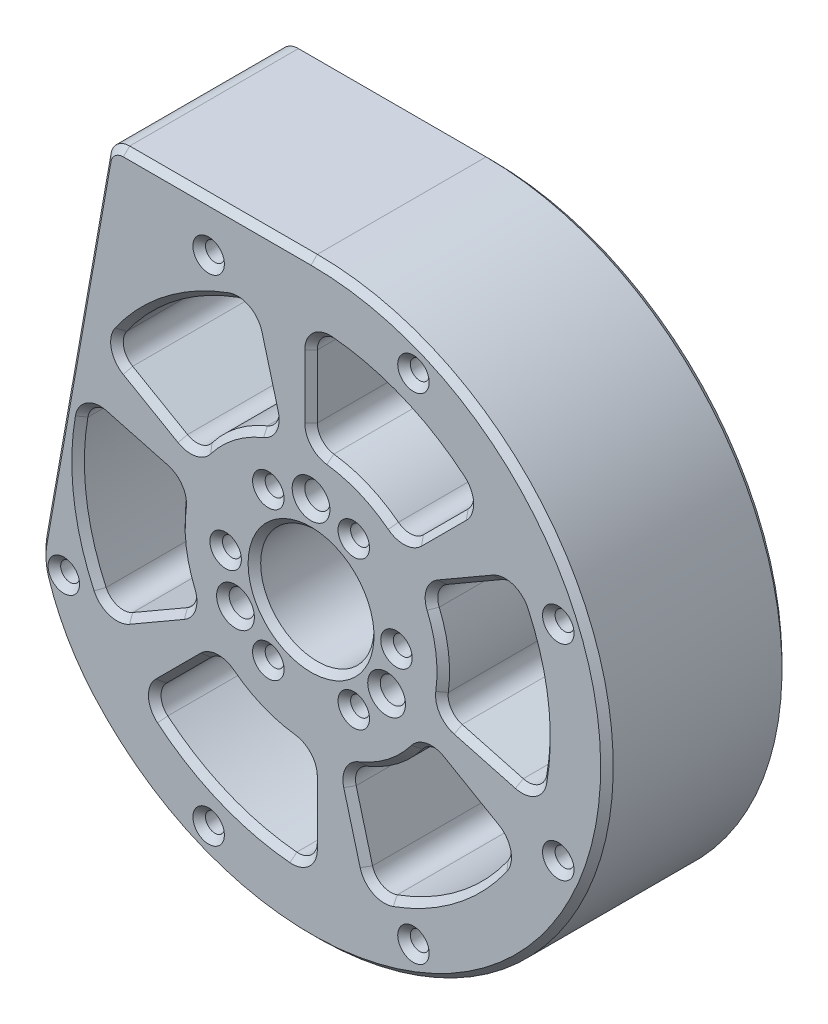
SolidWorks part; units mm, degrees
material "尼龙 101"
ref_plane "前视基准面" through (0, 0, 0) normal (0, 0, 1) x (1, 0, 0)
ref_plane "上视基准面" through (0, 0, 0) normal (0, 1, 0) x (1, 0, 0)
ref_plane "右视基准面" through (0, 0, 0) normal (1, 0, 0) x (0, 0, -1)
sketch "草图1" plane through (0, 0, 0) normal (0, 0, 1) x (1, 0, 0)
  line L0 (-29.8039, 47) -> (0, 47)
  line L1 (-75.3218, 47) -> (0, 47) construction
  line L3 (-32.7584, 44.5209) -> (-42.9535, -13.2986)
  line L6 (-43.3454, -15.5209) -> (-32.9421, 43.4791) construction
  line L7 (0, 23.8118) -> (0, 33.8674)
  line L8 (16.8375, 16.8375) -> (23.9479, 23.9479)
  line L9 (20.6216, 11.9059) -> (29.33, 16.9337)
  line L10 (23.0004, -6.1629) -> (32.7134, -8.7655)
  line L11 (20.6216, -11.9059) -> (29.33, -16.9337)
  line L12 (6.1629, -23.0004) -> (8.7655, -32.7134)
  line L13 (0, -23.8118) -> (0, -33.8674)
  line L14 (-16.8375, -16.8375) -> (-23.9479, -23.9479)
  line L15 (-20.6216, -11.9059) -> (-29.33, -16.9337)
  line L16 (-23.0004, 6.1629) -> (-32.7134, 8.7655)
  line L17 (-20.6216, 11.9059) -> (-29.33, 16.9337)
  line L18 (-6.1629, 23.0004) -> (-8.7655, 32.7134)
  arc A0 (0, 47) -> (-35.3098, -31.0197) centre (0, 0) cw
  circle A1 centre (16.264, 39.2649) radius 1.5
  circle A2 centre (16.264, 39.2649) radius 1.5
  circle A3 centre (-16.264, 39.2649) radius 1.5
  circle A4 centre (-16.264, 39.2649) radius 1.5
  circle A5 centre (-39.2649, -16.264) radius 1.5
  circle A6 centre (-39.2649, -16.264) radius 1.5
  circle A7 centre (-16.264, -39.2649) radius 1.5
  circle A8 centre (-16.264, -39.2649) radius 1.5
  circle A9 centre (16.264, -39.2649) radius 1.5
  circle A10 centre (16.264, -39.2649) radius 1.5
  circle A11 centre (39.2649, -16.264) radius 1.5
  circle A12 centre (39.2649, -16.264) radius 1.5
  circle A13 centre (39.2649, 16.264) radius 1.5
  circle A14 centre (39.2649, 16.264) radius 1.5
  circle A15 centre (0, 0) radius 9
  circle A16 centre (0, 0) radius 9
  circle A17 centre (-6.7839, 11.75) radius 1.5
  circle A18 centre (-6.7839, 11.75) radius 1.5
  circle A19 centre (6.7839, 11.75) radius 1.5
  circle A20 centre (6.7839, 11.75) radius 1.5
  circle A21 centre (-13.5677, 0) radius 1.5
  circle A22 centre (-13.5677, 0) radius 1.5
  circle A23 centre (-6.7839, -11.75) radius 1.5
  circle A24 centre (-6.7839, -11.75) radius 1.5
  circle A25 centre (6.7839, -11.75) radius 1.5
  circle A26 centre (6.7839, -11.75) radius 1.5
  circle A27 centre (13.5677, 0) radius 1.5
  circle A28 centre (13.5677, 0) radius 1.5
  circle A29 centre (0, 13.8564) radius 2
  circle A30 centre (0, 13.8564) radius 2
  circle A31 centre (12, -6.9282) radius 2
  circle A32 centre (12, -6.9282) radius 2
  circle A33 centre (-12, -6.9282) radius 2
  circle A34 centre (-12, -6.9282) radius 2
  arc A35 (-42.6326, -18.0737) -> (-35.3098, -31.0197) centre (-7.9999, -7.0279) ccw
  arc A37 (-29.8039, 47) -> (-32.7584, 44.5209) centre (-29.8039, 44) ccw
  arc A43 (-42.6326, -18.0737) -> (-42.9535, -13.2986) centre (-33.1054, -15.0351) cw
  circle A45 centre (0, 0) radius 21 construction
  circle A47 centre (0, 0) radius 37 construction
  arc A51 (3.2647, 36.8557) -> (23.7524, 28.3694) centre (0, 0) cw
  circle A52 centre (0, 0) radius 21 construction
  arc A53 (2.625, 20.8353) -> (12.8766, 16.5889) centre (0, 0) cw
  arc A54 (0, 33.8674) -> (3.2647, 36.8557) centre (3, 33.8674) cw
  arc A55 (0, 23.8118) -> (2.625, 20.8353) centre (3, 23.8118) ccw
  arc A56 (16.8375, 16.8375) -> (12.8766, 16.5889) centre (14.7161, 18.9588) cw
  arc A57 (23.9479, 23.9479) -> (23.7524, 28.3694) centre (21.8265, 26.0692) ccw
  arc A58 (29.33, 16.9337) -> (33.5503, 15.6005) centre (30.83, 14.3356) cw
  arc A59 (33.5503, 15.6005) -> (36.4448, -6.3855) centre (0, 0) cw
  arc A60 (32.7134, -8.7655) -> (36.4448, -6.3855) centre (33.4898, -5.8677) ccw
  arc A61 (23.0004, -6.1629) -> (20.8047, -2.857) centre (23.7769, -3.2652) cw
  arc A62 (19.3564, 8.1443) -> (20.8047, -2.857) centre (0, 0) cw
  arc A63 (20.6216, 11.9059) -> (19.3564, 8.1443) centre (22.1216, 9.3078) ccw
  arc A64 (29.33, -16.9337) -> (30.2856, -21.2552) centre (27.83, -19.5318) cw
  arc A65 (30.2856, -21.2552) -> (12.6924, -34.7549) centre (0, 0) cw
  arc A66 (8.7655, -32.7134) -> (12.6924, -34.7549) centre (11.6633, -31.9369) ccw
  arc A67 (6.1629, -23.0004) -> (7.9281, -19.4459) centre (9.0607, -22.2239) cw
  arc A68 (16.7314, -12.691) -> (7.9281, -19.4459) centre (0, 0) cw
  arc A69 (20.6216, -11.9059) -> (16.7314, -12.691) centre (19.1216, -14.504) ccw
  arc A70 (0, -33.8674) -> (-3.2647, -36.8557) centre (-3, -33.8674) cw
  arc A71 (-3.2647, -36.8557) -> (-23.7524, -28.3694) centre (0, 0) cw
  arc A72 (-23.9479, -23.9479) -> (-23.7524, -28.3694) centre (-21.8265, -26.0692) ccw
  arc A73 (-16.8375, -16.8375) -> (-12.8766, -16.5889) centre (-14.7161, -18.9588) cw
  arc A74 (-2.625, -20.8353) -> (-12.8766, -16.5889) centre (0, 0) cw
  arc A75 (0, -23.8118) -> (-2.625, -20.8353) centre (-3, -23.8118) ccw
  arc A76 (-29.33, -16.9337) -> (-33.5503, -15.6005) centre (-30.83, -14.3356) cw
  arc A77 (-33.5503, -15.6005) -> (-36.4448, 6.3855) centre (0, 0) cw
  arc A78 (-32.7134, 8.7655) -> (-36.4448, 6.3855) centre (-33.4898, 5.8677) ccw
  arc A79 (-23.0004, 6.1629) -> (-20.8047, 2.857) centre (-23.7769, 3.2652) cw
  arc A80 (-19.3564, -8.1443) -> (-20.8047, 2.857) centre (0, 0) cw
  arc A81 (-20.6216, -11.9059) -> (-19.3564, -8.1443) centre (-22.1216, -9.3078) ccw
  arc A82 (-29.33, 16.9337) -> (-30.2856, 21.2552) centre (-27.83, 19.5318) cw
  arc A83 (-30.2856, 21.2552) -> (-12.6924, 34.7549) centre (0, 0) cw
  arc A84 (-8.7655, 32.7134) -> (-12.6924, 34.7549) centre (-11.6633, 31.9369) ccw
  arc A85 (-6.1629, 23.0004) -> (-7.9281, 19.4459) centre (-9.0607, 22.2239) cw
  arc A86 (-16.7314, 12.691) -> (-7.9281, 19.4459) centre (0, 0) cw
  arc A87 (-20.6216, 11.9059) -> (-16.7314, 12.691) centre (-19.1216, 14.504) ccw
  point P65 (-32.3212, 47)
  point P68 (-43.3454, -15.5209)
  point P83 (0, 37)
  point P86 (0, 21)
  point P89 (14.8492, 14.8492)
  point P92 (26.163, 26.163)
  point P154 (0, 0)
  dimension "D18" = 3
  dimension "D19" = 10
  dimension "D21" = 74
  dimension "D23" = 3
  dimension "D22" = 45
  dimension "D1" = 0
  dimension "D2" = 0
  dimension "D3" = 0
  dimension "D4" = 0
  dimension "D5" = 0
  dimension "D6" = 0
  dimension "D7" = 0
  dimension "D8" = 0
  dimension "D9" = 0
  dimension "D10" = 0
  dimension "D11" = 0
  dimension "D12" = 0
  dimension "D13" = 0
  dimension "D14" = 0
  dimension "D15" = 0
  dimension "D16" = 0
  dimension "D17" = 0
  dimension "D24" = 6
extrude "凸台-拉伸1" add sketch "草图1" along normal blind 28.8
chamfer "倒角1" distance 1 angle 45 142 edges at (-10.2795, 34.5987, 0) (-7.4642, 27.8569, 0) (-6.3738, 20.8896, 0) (-12.784, 16.6604, 0) (-18.5281, 11.5632, 0) (-24.9758, 14.4198, 0) (-30.7593, 18.884, 0) (-22.5242, 29.3541, 0) (-35.1031, 8.397, 0) (-27.8569, 7.4642, 0) (-21.2778, 4.9249, 0) (-20.8203, -2.7411, 0) (-19.2781, -10.2642, 0) (-24.9758, -14.4198, 0) (-31.7337, -17.1963, 0) (-36.6835, -4.8295, 0) (-24.8236, -26.2017, 0) (-20.3927, -20.3927, 0) (-14.904, -15.9647, 0) (-8.0364, -19.4015, 0) (-0.75, -21.8274, 0) (0, -28.8396, 0) (-0.9744, -36.0803, 0) (-14.1593, -34.1835, 0) (10.2795, -34.5987, 0) (7.4642, -27.8569, 0) (6.3738, -20.8896, 0) (12.784, -16.6604, 0) (18.5281, -11.5632, 0) (24.9758, -14.4198, 0) (30.7593, -18.884, 0) (22.5242, -29.3541, 0) (35.1031, -8.397, 0) (27.8569, -7.4642, 0) (21.2778, -4.9249, 0) (20.8203, 2.7411, 0) (19.2781, 10.2642, 0) (24.9758, 14.4198, 0) (31.7337, 17.1963, 0) (36.6835, 4.8295, 0) (24.8236, 26.2017, 0) (20.3927, 20.3927, 0) (14.904, 15.9647, 0) (8.0364, 19.4015, 0) (0.75, 21.8274, 0) (0, 28.8396, 0) (0.9744, 36.0803, 0) (14.1593, 34.1835, 0) (-10, -6.9282, 0) (2, 13.8564, 0) (8.2839, -11.75, 0) (-12.0677, 0, 0) (-5.2839, 11.75, 0) (40.7649, 16.264, 0) (17.764, -39.2649, 0) (-37.7649, -16.264, 0) (17.764, 39.2649, 0) (-14.902, 47, 0) (-31.7323, 46.2981, 0) (-37.8559, 15.6112, 0) (-43.0829, -15.7057, 0) (-39.6404, -24.9252, 0) (42.8189, -19.3788, 0) (-14.764, 39.2649, 0) (-14.764, -39.2649, 0) (40.7649, -16.264, 0) (9, 0, 0) (8.2839, 11.75, 0) (-5.2839, -11.75, 0) (15.0677, 0, 0) (14, -6.9282, 0) (-24.9758, 14.4198, 28.8) (-18.5281, 11.5632, 28.8) (-12.784, 16.6604, 28.8) (-6.3738, 20.8896, 28.8) (-7.4642, 27.8569, 28.8) (-10.2795, 34.5987, 28.8) (-22.5242, 29.3541, 28.8) (-30.7593, 18.884, 28.8) (0, -28.8396, 28.8) (-0.75, -21.8274, 28.8) (-8.0364, -19.4015, 28.8) (-14.904, -15.9647, 28.8) (-20.3927, -20.3927, 28.8) (-24.8236, -26.2017, 28.8) (-14.1593, -34.1835, 28.8) (-0.9744, -36.0803, 28.8) (24.9758, 14.4198, 28.8) (19.2781, 10.2642, 28.8) (20.8203, 2.7411, 28.8) (21.2778, -4.9249, 28.8) (27.8569, -7.4642, 28.8) (35.1031, -8.397, 28.8) (36.6835, 4.8295, 28.8) (31.7337, 17.1963, 28.8) (-10, -6.9282, 28.8) (14, -6.9282, 28.8) (2, 13.8564, 28.8) (15.0677, 0, 28.8) (8.2839, -11.75, 28.8) (-5.2839, -11.75, 28.8) (-12.0677, 0, 28.8) (8.2839, 11.75, 28.8) (-5.2839, 11.75, 28.8) (9, 0, 28.8) (40.7649, 16.264, 28.8) (40.7649, -16.264, 28.8) (17.764, -39.2649, 28.8) (-14.764, -39.2649, 28.8) (-37.7649, -16.264, 28.8) (-14.764, 39.2649, 28.8) (17.764, 39.2649, 28.8) (-39.6404, -24.9252, 28.8) (-43.0829, -15.7057, 28.8) (-37.8559, 15.6112, 28.8) (-31.7323, 46.2981, 28.8) (-14.902, 47, 28.8) (42.8189, -19.3788, 28.8) (0, 28.8396, 28.8) (0.75, 21.8274, 28.8) (8.0364, 19.4015, 28.8) (14.904, 15.9647, 28.8) (20.3927, 20.3927, 28.8) (24.8236, 26.2017, 28.8) (14.1593, 34.1835, 28.8) (0.9744, 36.0803, 28.8) (24.9758, -14.4198, 28.8) (18.5281, -11.5632, 28.8) (12.784, -16.6604, 28.8) (6.3738, -20.8896, 28.8) (7.4642, -27.8569, 28.8) (10.2795, -34.5987, 28.8) (22.5242, -29.3541, 28.8) (30.7593, -18.884, 28.8) (-24.9758, -14.4198, 28.8) (-19.2781, -10.2642, 28.8) (-20.8203, -2.7411, 28.8) (-21.2778, 4.9249, 28.8) (-27.8569, 7.4642, 28.8) (-35.1031, 8.397, 28.8) (-36.6835, -4.8295, 28.8) (-31.7337, -17.1963, 28.8)
